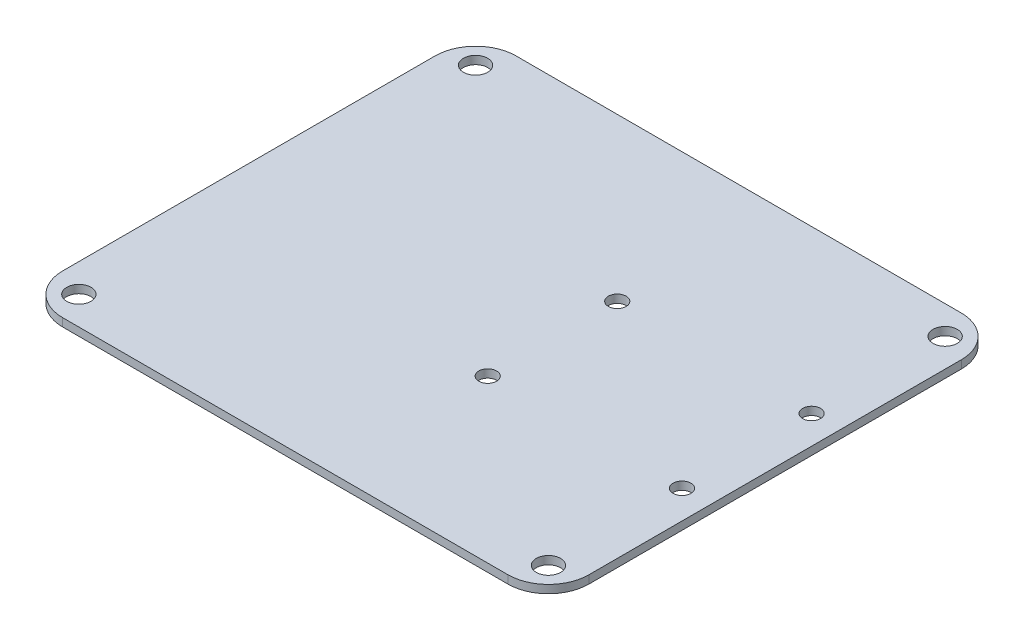
SolidWorks part; units mm, degrees
ref_plane "Front Plane" through (0, 0, 0) normal (0, 0, 1) x (1, 0, 0)
ref_plane "Top Plane" through (0, 0, 0) normal (0, 1, 0) x (1, 0, 0)
ref_plane "Right Plane" through (0, 0, 0) normal (1, 0, 0) x (0, 0, -1)
sketch "Sketch1" plane through (0, 0, 0) normal (0, 1, 0) x (1, 0, 0)
  line L0 (0, 0) -> (58, 0)
  line L1 (58, 0) -> (58, -49)
  line L2 (0, 0) -> (0, -49)
  line L3 (0, -49) -> (58, -49)
  line L4 (0, 0) -> (0, 3.5)
  line L5 (0, 3.5) -> (-3.5, 3.5)
  line L6 (58, -49) -> (61.5, -49)
  line L7 (61.5, -49) -> (61.5, -52.5)
  line L8 (0, -24.5) -> (58, -24.5)
  line L9 (-3.5, 3.5) -> (61.5, 3.5)
  line L10 (-3.5, 3.5) -> (-3.5, -52.5)
  line L11 (-3.5, -52.5) -> (61.5, -52.5)
  line L12 (61.5, 3.5) -> (61.5, -52.5)
  line L13 (58, -24.5) -> (58, -16.5)
  line L14 (58, -24.5) -> (58, -32.5)
  line L15 (58, -32.5) -> (34, -32.5)
  line L16 (34, -32.5) -> (34, -16.5)
  line L17 (34, -16.5) -> (58, -16.5)
  circle A0 centre (0, 0) radius 1.5
  circle A1 centre (58, 0) radius 1.5
  circle A2 centre (0, -49) radius 1.5
  circle A3 centre (58, -49) radius 1.5
  circle A4 centre (34, -16.5) radius 1.1
  circle A5 centre (58, -16.5) radius 1.1
  circle A6 centre (34, -32.5) radius 1.1
  circle A7 centre (58, -32.5) radius 1.1
extrude "Boss-Extrude1" add sketch "Sketch1" along normal blind 1 contours A5 L1 A1 L0 A0 L2 L8 L16 A4 L17 | A5 L17 A4 L16 L8 L13 | A7 L1 L8 L16 A6 L15 | A7 L15 A6 L16 L8 L2 A2 L3 A3 L1 | A7 L1 A3 L6 L12 L9 L4 A0 L0 A1 A5 L13 | A3 L3 A2 L2 A0 L4 L5 L10 L11 L7 L6
fillet "Fillet2" radius 5 4 edges at (61.5, 0.5, 52.5) (61.5, 0.5, -3.5) (-3.5, 0.5, -3.5) (-3.5, 0.5, 52.5)
